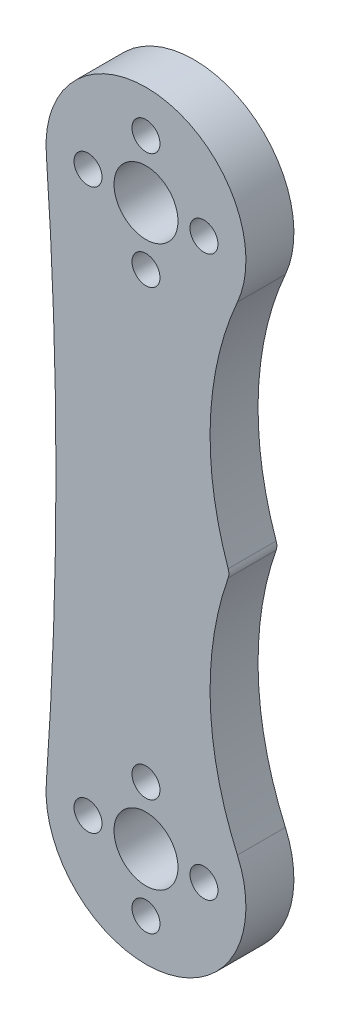
SolidWorks part; units mm, degrees
ref_plane "Front Plane" through (0, 0, 0) normal (0, 0, 1) x (1, 0, 0)
ref_plane "Top Plane" through (0, 0, 0) normal (0, 1, 0) x (1, 0, 0)
ref_plane "Right Plane" through (0, 0, 0) normal (1, 0, 0) x (0, 0, -1)
sketch "Sketch1" plane through (0, 0, 0) normal (0, 0, 1) x (1, 0, 0)
  circle A0 centre (0, 0) radius 12.5
  circle A1 centre (0, 70) radius 12.5
  circle A3 centre (48.015, 48.7676) radius 40
  circle A4 centre (48.015, 21.2324) radius 40
  circle A5 centre (8.8652, 35) radius 1.5
  circle A7 centre (-492.4582, 35) radius 481.2004
  dimension "D1" = 25
  dimension "D2" = 25
  dimension "D4" = 3
  dimension "D6" = 80
  dimension "D7" = 80
  dimension "D3" = 70
  dimension "D5" = 35
extrude "Boss-Extrude1" add sketch "Sketch1" along normal blind 6
sketch "Sketch2" plane through (0, 0, 6) normal (0, 0, 1) x (1, 0, 0)
  circle A0 centre (0, 70) radius 4
  circle A1 centre (0, 0) radius 4
  circle A2 centre (0, 7.25) radius 1.75
  circle A3 centre (7.25, 0) radius 1.75
  circle A4 centre (0, -7.25) radius 1.75
  circle A5 centre (-7.25, 0) radius 1.75
  circle A6 centre (0, 77.25) radius 1.75
  circle A7 centre (7.25, 70) radius 1.75
  circle A8 centre (0, 62.75) radius 1.75
  circle A9 centre (-7.25, 70) radius 1.75
  point P17 (0, 0)
  point P26 (0, 70)
  dimension "D1" = 8
  dimension "D2" = 8
  dimension "D3" = 7.25
  dimension "D5" = 3.5
  dimension "D8" = 3.5
  dimension "D6" = 7.25
  dimension "D4" = 4
  dimension "D7" = 4
extrude "Cut-Extrude1" cut sketch "Sketch2" against normal through all
